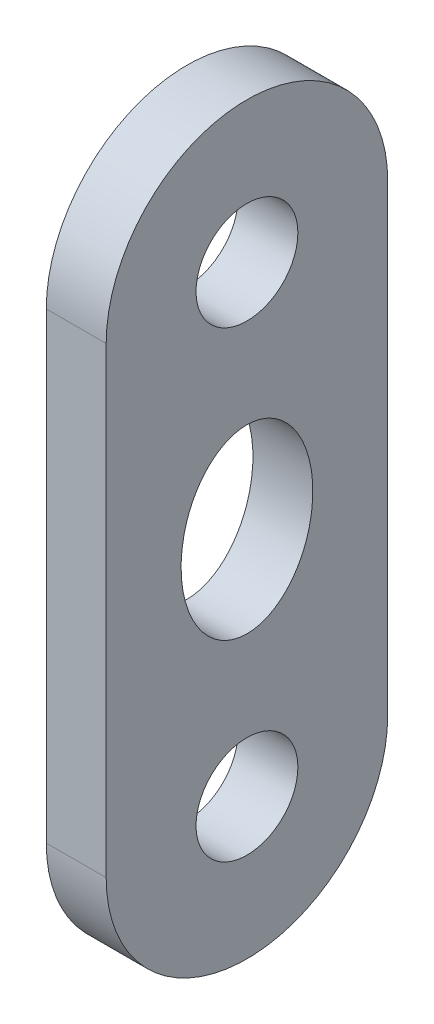
SolidWorks part; units mm, degrees
ref_plane "Front Plane" through (0, 0, 0) normal (0, 0, 1) x (1, 0, 0)
ref_plane "Top Plane" through (0, 0, 0) normal (0, 1, 0) x (1, 0, 0)
ref_plane "Right Plane" through (0, 0, 0) normal (1, 0, 0) x (0, 0, -1)
sketch "Sketch1" plane through (0, 0, 0) normal (1, 0, 0) x (0, 0, -1)
  line L0 (0, -15.4439) -> (0, 0) construction
  line L1 (-4.7, -15.4439) -> (-4.7, 0)
  line L2 (4.7, -15.4439) -> (4.7, 0)
  line L3 (-4.746, -14.6966) -> (0, 0) construction
  line L4 (1.7, 0) -> (4.7, 0) construction
  line L5 (-2.2, -7.722) -> (0, -7.722) construction
  arc A0 (-4.7, -15.4439) -> (4.7, -15.4439) centre (0, -15.4439) ccw
  arc A1 (4.7, 0) -> (-4.7, 0) centre (0, 0) ccw
  circle A2 centre (0, 0) radius 1.5 construction
  circle A3 centre (0, 0) radius 4.7 construction
  circle A4 centre (0, 0) radius 1.7
  circle A5 centre (0, -15.4439) radius 1.7
  ellipse E0 centre (0, -7.722) end of major axis (0, -10.7439) minor radius 2.2
  point P2 (0, -7.722)
  dimension "D2" = 3
  dimension "D3" = 3
  dimension "D4" = 2.2
  dimension "D1" = 0.2
extrude "Boss-Extrude1" add sketch "Sketch1" along normal blind 2
equation "\"Tolerance\"=0.2"
equation "\"D1@Sketch1\"=\"Tolerance\""
